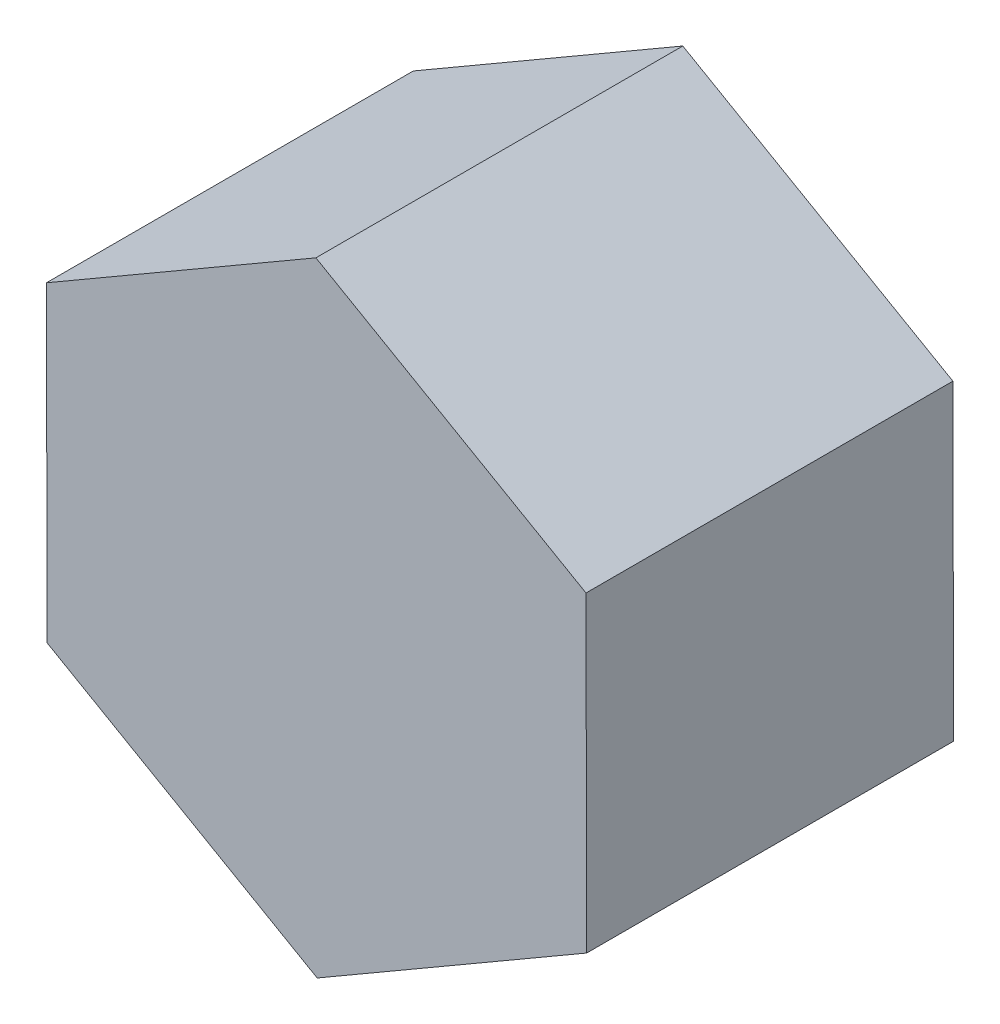
SolidWorks part; units mm, degrees
material "Brass"
ref_plane "Front Plane" through (0, 0, 0) normal (0, 0, 1) x (1, 0, 0)
ref_plane "Top Plane" through (0, 0, 0) normal (0, 1, 0) x (1, 0, 0)
ref_plane "Right Plane" through (0, 0, 0) normal (1, 0, 0) x (0, 0, -1)
sketch "Sketch1" plane through (0, 0, 0) normal (0, 0, 1) x (1, 0, 0)
  line L1 (6.3577, -3.6528) -> (6.3423, 3.6795)
  line L2 (6.3423, 3.6795) -> (-0.0154, 7.3323)
  line L3 (-0.0154, 7.3323) -> (-6.3577, 3.6528)
  line L4 (-6.3577, 3.6528) -> (-6.3423, -3.6795)
  line L5 (-6.3423, -3.6795) -> (0.0154, -7.3323)
  line L6 (0.0154, -7.3323) -> (6.3577, -3.6528)
  circle A0 centre (0, 0) radius 6.35 construction
  dimension "D1" = 12.7
extrude "Boss-Extrude1" add sketch "Sketch1" along normal blind 8.636
